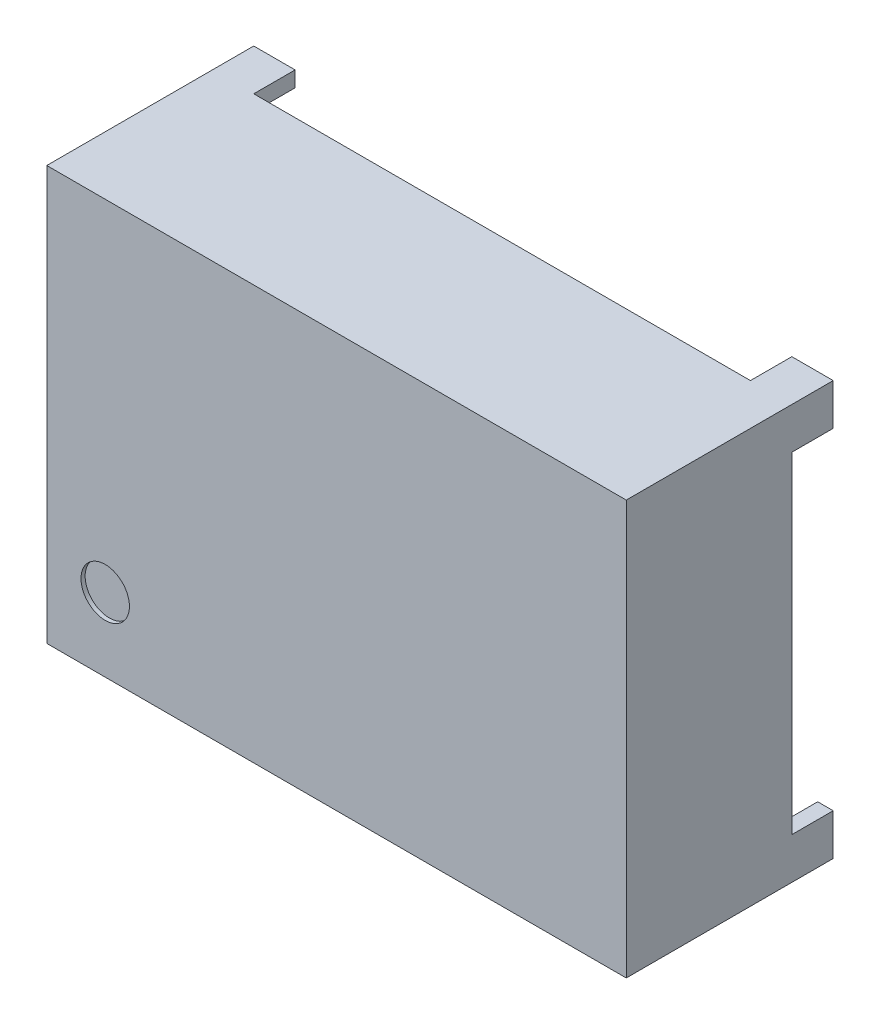
SolidWorks part; units mm, degrees
ref_plane "前视基准面" through (0, 0, 0) normal (0, 0, 1) x (1, 0, 0)
ref_plane "上视基准面" through (0, 0, 0) normal (0, 1, 0) x (1, 0, 0)
ref_plane "右视基准面" through (0, 0, 0) normal (1, 0, 0) x (0, 0, -1)
sketch "草图1" plane through (0, 0, 0) normal (0, 0, 1) x (1, 0, 0)
  line L0 (0, 26.8912) -> (0, -30.9887) construction
  line L1 (-14, 10) -> (14, 10)
  line L2 (-14, 10) -> (-14, -10)
  line L3 (-14, -10) -> (14, -10)
  line L4 (14, 10) -> (14, -10)
  line L5 (-33.696, 0) -> (28.6691, 0) construction
  dimension "D1" = 20
  dimension "D2" = 28
extrude "拉伸1" add sketch "草图1" along normal blind 8
sketch "草图2" plane through (0, 0, 0) normal (0, 0, -1) x (-1, 0, 0)
  line L0 (-14, 10) -> (-14, 8)
  line L1 (-14, -10) -> (-14, 10) construction
  line L2 (-14, 8) -> (-13.25, 8)
  line L3 (-13.25, 8) -> (-13.25, 9.25)
  line L4 (-13.25, 9.25) -> (-12, 9.25)
  line L5 (-12, 9.25) -> (-12, 10)
  line L6 (-14, 10) -> (14, 10) construction
  line L7 (-12, 10) -> (-14, 10)
  line L8 (0, 13.9401) -> (0, -13.2305) construction
  line L9 (18.5604, 0) -> (-19.4281, 0) construction
  line L10 (12, 10) -> (14, 10)
  line L11 (12, 9.25) -> (12, 10)
  line L12 (13.25, 9.25) -> (12, 9.25)
  line L13 (13.25, 8) -> (13.25, 9.25)
  line L14 (14, 8) -> (13.25, 8)
  line L15 (14, 10) -> (14, 8)
  line L16 (-12, -10) -> (-14, -10)
  line L17 (-12, -9.25) -> (-12, -10)
  line L18 (-13.25, -9.25) -> (-12, -9.25)
  line L19 (-13.25, -8) -> (-13.25, -9.25)
  line L20 (-14, -8) -> (-13.25, -8)
  line L21 (-14, -10) -> (-14, -8)
  line L22 (14, -10) -> (14, -8)
  line L23 (14, -8) -> (13.25, -8)
  line L24 (13.25, -8) -> (13.25, -9.25)
  line L25 (13.25, -9.25) -> (12, -9.25)
  line L26 (12, -9.25) -> (12, -10)
  line L27 (12, -10) -> (14, -10)
  dimension "D1" = 2
  dimension "D2" = 2
  dimension "D3" = 0.75
  dimension "D4" = 0.75
extrude "拉伸2" add sketch "草图2" along normal blind 2
sketch "草图3" plane through (0, 0, 8) normal (0, 0, 1) x (1, 0, 0)
  circle A0 centre (-11.1773, -6.4535) radius 1.1701
extrude "切除-拉伸1" cut sketch "草图3" against normal blind 0.2
